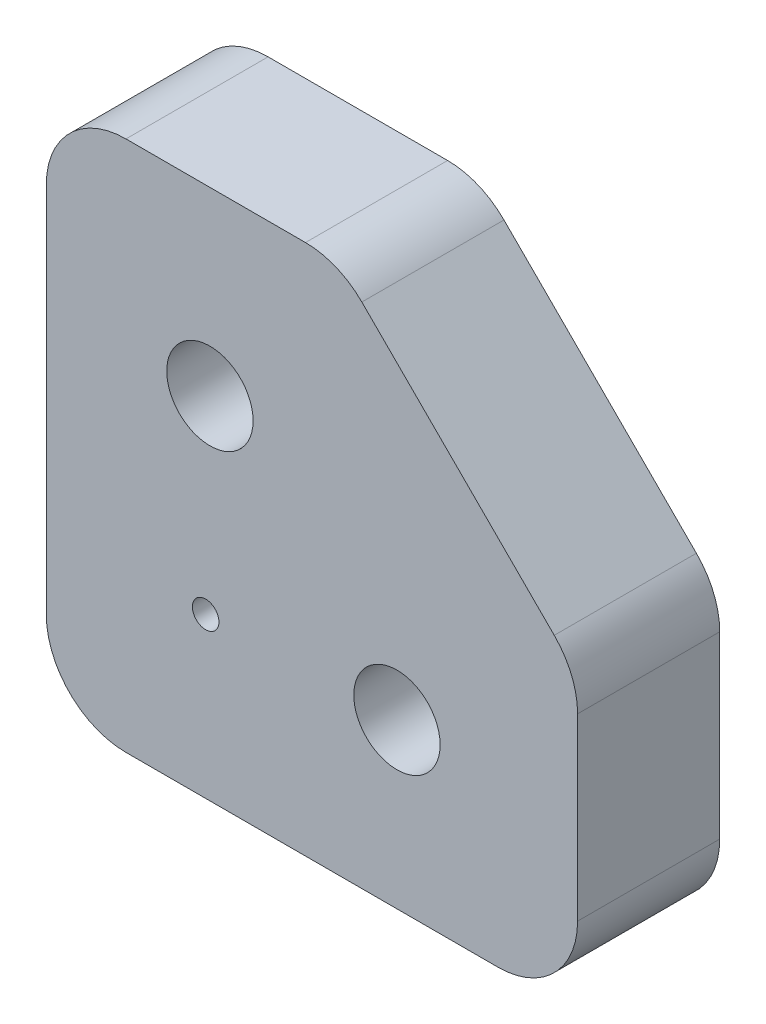
SolidWorks part; units mm, degrees
ref_plane "Front Plane" through (0, 0, 0) normal (0, 0, 1) x (1, 0, 0)
ref_plane "Top Plane" through (0, 0, 0) normal (0, 1, 0) x (1, 0, 0)
ref_plane "Right Plane" through (0, 0, 0) normal (1, 0, 0) x (0, 0, -1)
sketch "Model" plane through (0, 0, 0) normal (0, 0, 1) x (1, 0, 0)
  line L468 (0, 17) -> (0, 3)
  line L469 (9.7574, 20) -> (3, 20)
  line L470 (19.1213, 11.8787) -> (11.8787, 19.1213)
  line L471 (20, 3) -> (20, 9.7574)
  line L472 (3, 0) -> (17, 0)
  arc A50 (3, 20) -> (0, 17) centre (3, 17) ccw
  arc A51 (11.8787, 19.1213) -> (9.7574, 20) centre (9.7574, 17) ccw
  arc A52 (20, 9.7574) -> (19.1213, 11.8787) centre (17, 9.7574) ccw
  arc A53 (17, 0) -> (20, 3) centre (17, 3) ccw
  arc A54 (0, 3) -> (3, 0) centre (3, 3) ccw
  circle A55 centre (6, 6) radius 0.5
  circle A56 centre (13.2, 6.16) radius 1.625
  circle A57 centre (6.16, 13.2) radius 1.625
  circle A58 centre (6.16, 13.2) radius 1.2
  circle A59 centre (13.2, 6.16) radius 1.2
extrude "Boss-Extrude1" add sketch "Model" along normal blind 5.35 contours L468 A54 L472 A53 L471 A52 L470 A51 L469 A50 A57 A56 A55
